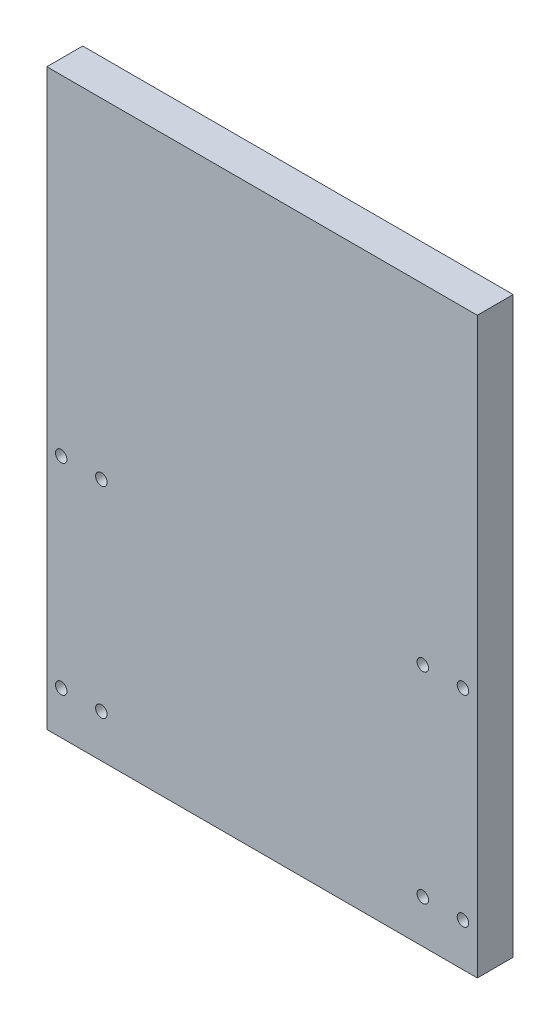
SolidWorks part; units mm, degrees
material "Balsa"
ref_plane "Front" through (0, 0, 0) normal (0, 0, 1) x (1, 0, 0)
ref_plane "Top" through (0, 0, 0) normal (0, 1, 0) x (1, 0, 0)
ref_plane "Right" through (0, 0, 0) normal (1, 0, 0) x (0, 0, -1)
sketch "Sketch1" plane through (0, 0, 0) normal (0, 0, 1) x (1, 0, 0)
  line L0 (0, 213.5111) -> (0, -303.9575) construction
  line L1 (-150, 200) -> (150, 200)
  line L2 (-150, 200) -> (-150, -200)
  line L3 (-150, -200) -> (150, -200)
  line L4 (150, 200) -> (150, -200)
  line L5 (-150, 200) -> (150, -200) construction
  line L6 (-150, -200) -> (150, 200) construction
  line L7 (-285.7834, -100) -> (200.0602, -100) construction
  circle A0 centre (-112, -170) radius 4
  circle A1 centre (-140, -170) radius 4
  circle A2 centre (112, -170) radius 4
  circle A3 centre (140, -170) radius 4
  circle A4 centre (112, -30) radius 4
  circle A5 centre (140, -30) radius 4
  circle A6 centre (-112, -30) radius 4
  circle A7 centre (-140, -30) radius 4
  point P0 (0, 0)
  dimension "D4" = 8
  dimension "D5" = 10
  dimension "D6" = 28
  dimension "D1" = 400
  dimension "D2" = 300
  dimension "D3" = 30
  dimension "D7" = 100
extrude "Boss-Extrude1" add sketch "Sketch1" against normal blind 25
